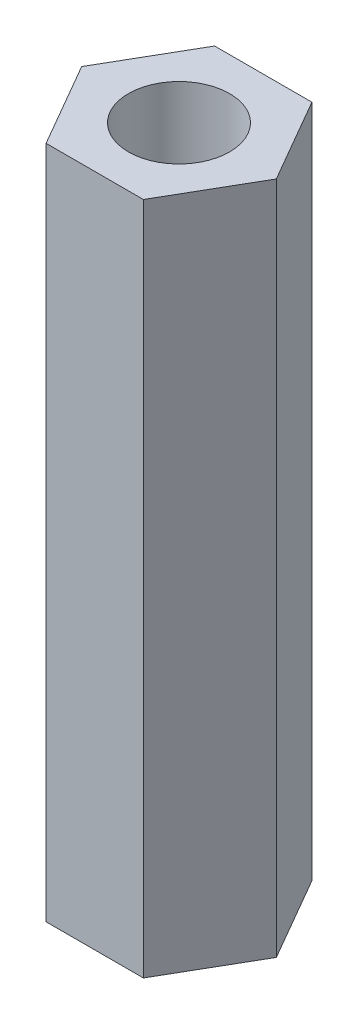
SolidWorks part; units mm, degrees
ref_plane "Front Plane" through (0, 0, 0) normal (0, 0, 1) x (1, 0, 0)
ref_plane "Top Plane" through (0, 0, 0) normal (0, 1, 0) x (1, 0, 0)
ref_plane "Right Plane" through (0, 0, 0) normal (1, 0, 0) x (0, 0, -1)
sketch "Sketch1" plane through (0, 0, 0) normal (0, 1, 0) x (1, 0, 0)
  line L1 (1.4434, 2.5) -> (-1.4434, 2.5)
  line L2 (-1.4434, 2.5) -> (-2.8868, 0)
  line L3 (-2.8868, 0) -> (-1.4434, -2.5)
  line L4 (-1.4434, -2.5) -> (1.4434, -2.5)
  line L5 (1.4434, -2.5) -> (2.8868, 0)
  line L6 (2.8868, 0) -> (1.4434, 2.5)
  circle A0 centre (0, 0) radius 2.5 construction
  circle A1 centre (0, 0) radius 1.5
  dimension "D1" = 5
  dimension "D2" = 3
extrude "Boss-Extrude1" add sketch "Sketch1" along normal blind 20
